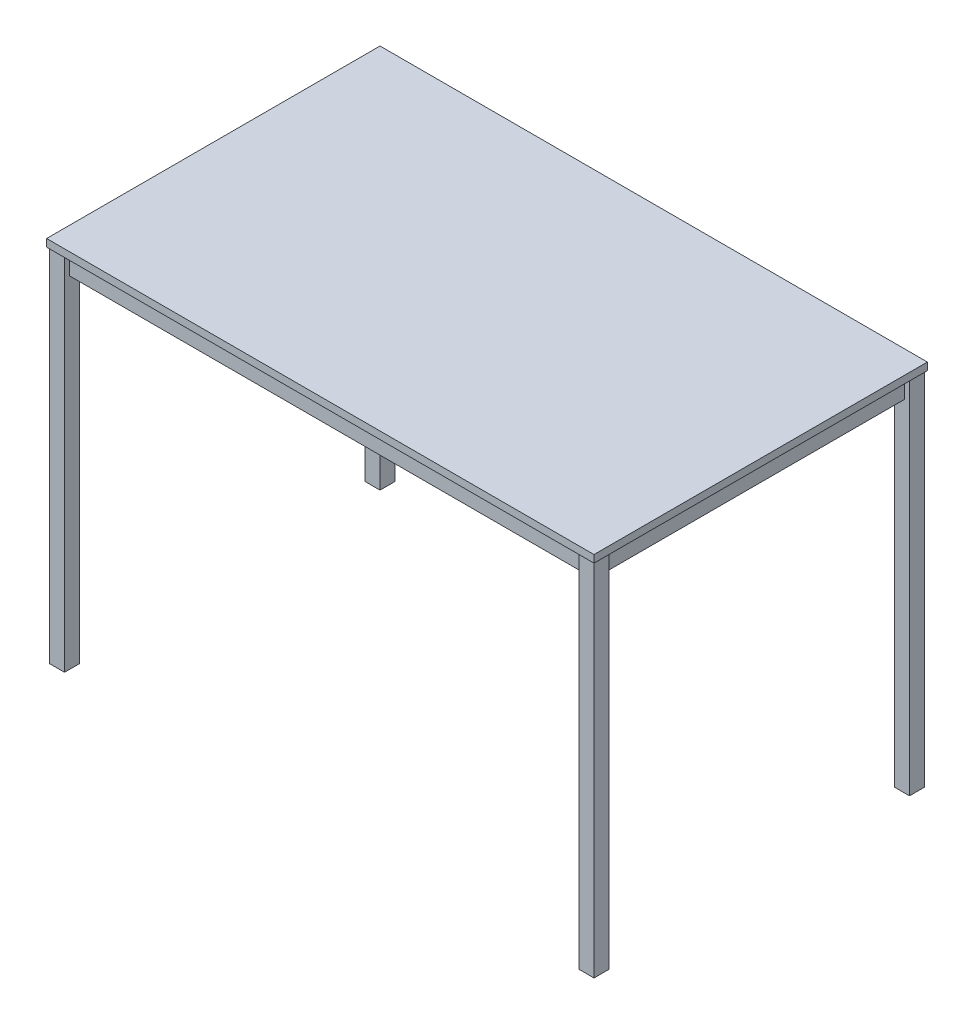
SolidWorks part; units mm, degrees
ref_plane "Front Plane" through (0, 0, 0) normal (0, 0, 1) x (1, 0, 0)
ref_plane "Top Plane" through (0, 0, 0) normal (0, 1, 0) x (1, 0, 0)
ref_plane "Right Plane" through (0, 0, 0) normal (1, 0, 0) x (0, 0, -1)
sketch "Sketch1" plane through (0, 0, 0) normal (0, 1, 0) x (1, 0, 0)
  line L0 (0, -55) -> (0, 55) construction
  line L1 (-550, 335) -> (550, 335)
  line L2 (-550, 335) -> (-550, -335)
  line L3 (-550, -335) -> (550, -335)
  line L4 (550, 335) -> (550, -335)
  line L5 (-55, 0) -> (55, 0) construction
  dimension "D1" = 1100
  dimension "D2" = 550
  dimension "D3" = 670
  dimension "D4" = 335
extrude "Boss-Extrude1" add sketch "Sketch1" along normal blind 15
sketch "Sketch2" plane through (0, 0, 0) normal (0, 1, 0) x (1, 0, 0)
  line L0 (-550, 335) -> (-550, -335) construction
  line L1 (-547, -332) -> (-517, -332)
  line L2 (-547, -332) -> (-547, -302)
  line L3 (-547, -302) -> (-517, -302)
  line L4 (-517, -332) -> (-517, -302)
  line L5 (-550, -335) -> (550, -335) construction
  dimension "D1" = 30
  dimension "D2" = 30
  dimension "D3" = 3
  dimension "D4" = 3
extrude "Boss-Extrude2" add sketch "Sketch2" against normal blind 725
mirror "Mirror1" about plane through (0, 0, 0) normal (0, 0, 1) of "Boss-Extrude2"
mirror "Mirror2" about plane through (0, 0, 0) normal (1, 0, 0) of "Boss-Extrude2", "Mirror1"
sketch "Sketch3" plane through (0, 0, -302) normal (0, 0, 1) x (1, 0, 0)
  line L1 (-517, 0) -> (-537, 0)
  line L2 (-517, 0) -> (-517, -40)
  line L3 (-517, -40) -> (-537, -40)
  line L4 (-537, 0) -> (-537, -40)
  dimension "D1" = 20
  dimension "D2" = 40
extrude "Boss-Extrude3" add sketch "Sketch3" along normal up to body
mirror "Mirror3" about plane through (0, 0, 0) normal (1, 0, 0) of "Boss-Extrude3"
sketch "Sketch4" plane through (-517, 0, 0) normal (1, 0, 0) x (0, 0, -1)
  line L0 (-332, 0) -> (332, 0) construction
  line L1 (-302, -40) -> (-322, -40)
  line L2 (-302, -40) -> (-302, 0)
  line L3 (-302, 0) -> (-322, 0)
  line L4 (-322, -40) -> (-322, 0)
  dimension "D1" = 20
extrude "Boss-Extrude4" add sketch "Sketch4" along normal up to body
mirror "Mirror4" about plane through (0, 0, 0) normal (0, 0, 1) of "Boss-Extrude4"
